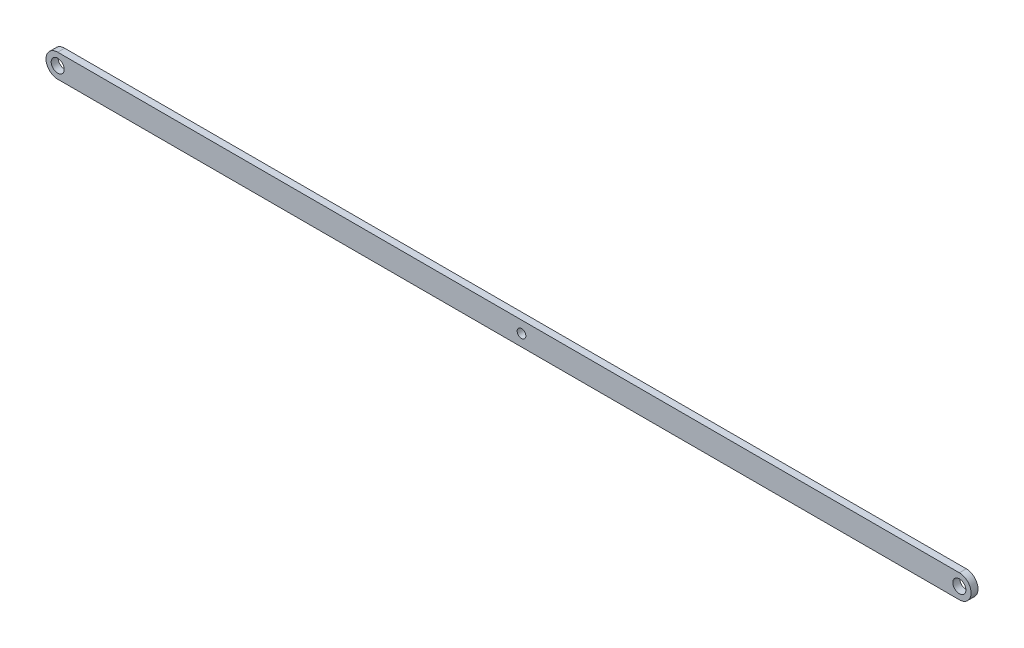
SolidWorks part; units mm, degrees
ref_plane "Front Plane" through (0, 0, 0) normal (0, 0, 1) x (1, 0, 0)
ref_plane "Top Plane" through (0, 0, 0) normal (0, 1, 0) x (1, 0, 0)
ref_plane "Right Plane" through (0, 0, 0) normal (1, 0, 0) x (0, 0, -1)
sketch "Sketch1" plane through (0, 0, 0) normal (0, 0, 1) x (1, 0, 0)
  line L0 (-3250, 0) -> (3250, 0) construction
  line L1 (-3250, 84.375) -> (3250, 84.375)
  line L2 (-3250, -84.375) -> (3250, -84.375)
  arc A0 (-3250, 84.375) -> (-3250, -84.375) centre (-3250, 0) ccw
  arc A1 (3250, -84.375) -> (3250, 84.375) centre (3250, 0) ccw
  circle A2 centre (-3250, 0) radius 46.875
  circle A3 centre (93.4186, 0) radius 31.25
  circle A4 centre (3250, 0) radius 46.875
  point P2 (0, 0)
  dimension "D3" = 84.375
  dimension "D4" = 93.75
  dimension "D1" = 6500
extrude "Boss-Extrude1" add sketch "Sketch1" along normal blind 50
